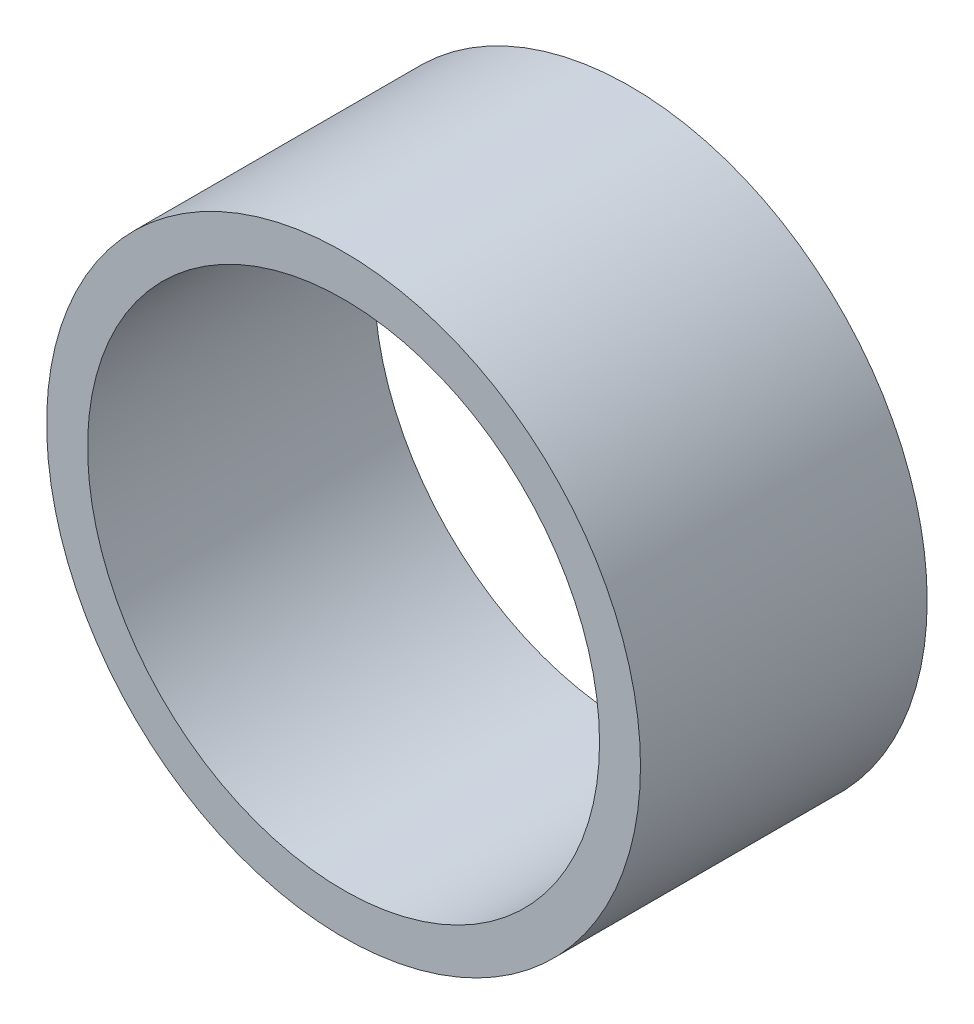
SolidWorks part; units mm, degrees
ref_plane "正面" through (0, 0, 0) normal (0, 0, 1) x (1, 0, 0)
ref_plane "平面" through (0, 0, 0) normal (0, 1, 0) x (1, 0, 0)
ref_plane "右側面" through (0, 0, 0) normal (1, 0, 0) x (0, 0, -1)
sketch "ｽｹｯﾁ1" plane through (0, 0, 0) normal (0, 0, 1) x (1, 0, 0)
  circle A0 centre (0, 0) radius 3.125
  circle A1 centre (0, 0) radius 3.625
  dimension "D1" = 6.25
  dimension "D2" = 7.25
extrude "ﾎﾞｽ - 押し出し1" add sketch "ｽｹｯﾁ1" along normal blind 3.5
